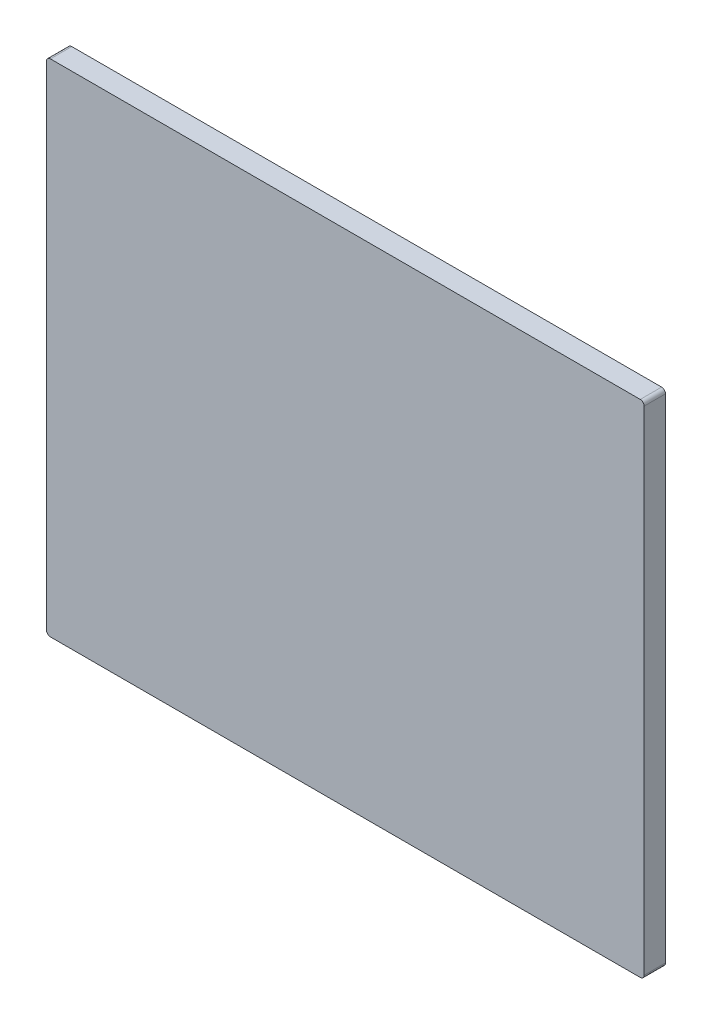
SolidWorks part; units mm, degrees
ref_plane "前视基准面" through (0, 0, 0) normal (0, 0, 1) x (1, 0, 0)
ref_plane "上视基准面" through (0, 0, 0) normal (0, 1, 0) x (1, 0, 0)
ref_plane "右视基准面" through (0, 0, 0) normal (1, 0, 0) x (0, 0, -1)
sketch "草图1" plane through (0, 0, 0) normal (0, 0, 1) x (1, 0, 0)
  line L1 (-154, -129) -> (154, -129)
  line L2 (-154, -129) -> (-154, 129)
  line L3 (-154, 129) -> (154, 129)
  line L4 (154, -129) -> (154, 129)
  line L5 (-154, -129) -> (154, 129) construction
  line L6 (-154, 129) -> (154, -129) construction
  point P0 (0, 0)
  dimension "D1" = 308
  dimension "D2" = 258
extrude "凸台-拉伸1" add sketch "草图1" along normal blind 11
fillet "圆角1" radius 2 4 edges at (-154, -129, 5.5) (154, -129, 5.5) (154, 129, 5.5) (-154, 129, 5.5)
